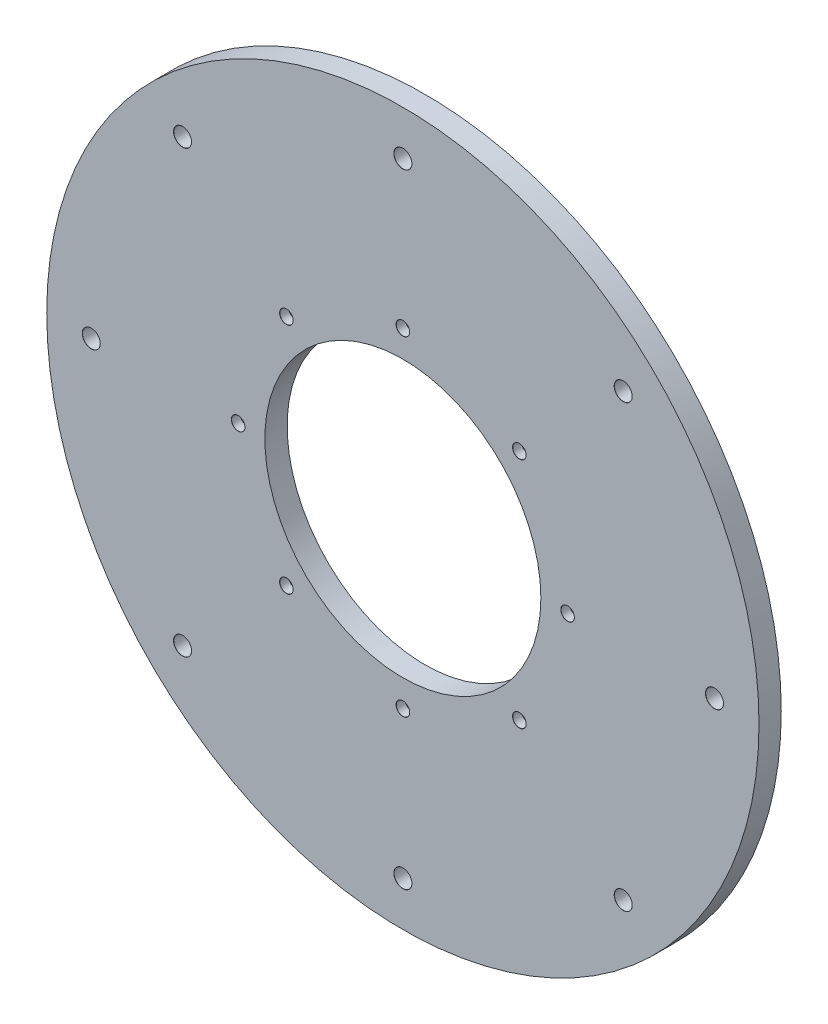
SolidWorks part; units mm, degrees
material "1.0503 (C45)"
ref_plane "Front Plane" through (0, 0, 0) normal (0, 0, 1) x (1, 0, 0)
ref_plane "Top Plane" through (0, 0, 0) normal (0, 1, 0) x (1, 0, 0)
ref_plane "Right Plane" through (0, 0, 0) normal (1, 0, 0) x (0, 0, -1)
sketch "Sketch2" plane through (0, 0, 0) normal (0, 0, 1) x (1, 0, 0)
  line L0 (0, 0) -> (0, 90.7247) construction
  circle A0 centre (0, 0) radius 80
  circle A1 centre (0, 0) radius 31
  point P0 (0, 0)
  point P4 (0, 70)
  point P5 (49.4975, 49.4975)
  point P8 (70, 0)
  point P9 (49.4975, -49.4975)
  point P10 (0, -70)
  point P11 (-49.4975, -49.4975)
  point P12 (-70, 0)
  point P13 (-49.4975, 49.4975)
  point P14 (0, 0)
  dimension "D3" = 160
  dimension "D4" = 62
  dimension "D1" = 70
  dimension "D2" = 8
extrude "Boss-Extrude1" add sketch "Sketch2" along normal blind 5
sketch "Sketch9" plane through (0, 0, 0) normal (0, 0, 1) x (1, 0, 0)
  line L0 (0, 0) -> (0, 90.7247) construction
  circle A0 centre (0, 0) radius 80
  circle A1 centre (0, 0) radius 31
  point P0 (0, 0)
  point P4 (0, 70)
  point P5 (49.4975, 49.4975)
  point P8 (70, 0)
  point P9 (49.4975, -49.4975)
  point P10 (0, -70)
  point P11 (-49.4975, -49.4975)
  point P12 (-70, 0)
  point P13 (-49.4975, 49.4975)
  point P14 (0, 0)
  dimension "D3" = 160
  dimension "D4" = 62
  dimension "D1" = 70
  dimension "D2" = 8
hole_wizard "Ø4.0mm Dowel Hole1" positions "Sketch10" profile "Sketch11" hole size "Ø4.0" standard "ISO"
sketch "Sketch10" plane through (0, 0, 5) normal (0, 0, 1) x (1, 0, 0)
  point P0 (0, 70)
  point P3 (-49.4975, 49.4975)
  point P6 (-70, 0)
  point P9 (-49.4975, -49.4975)
  point P12 (0, -70)
  point P15 (49.4975, -49.4975)
  point P18 (70, 0)
  point P21 (49.4975, 49.4975)
sketch "Sketch11" plane through (0, 70, 5) normal (1, 0, 0) x (0, -1, 0)
  line L0 (0, 0) -> (0, 6.2007)
  line L1 (0, 6.2007) -> (2, 4.999)
  line L2 (2, 4.999) -> (2, 0.025)
  line L3 (2, 0.025) -> (2.025, 0)
  line L5 (2.025, 0) -> (0, 0)
  line L6 (-2, 0.025) -> (-2.025, 0) construction
  line L10 (0, 6.2007) -> (-2, 4.999) construction
  line L11 (0, -6.35) -> (0, 107.95) construction
  dimension "Hole Dia." = 4
  dimension "Hole Depth" = 4.999
  dimension "Near C'Sink Dia." = 4.05
  dimension "Near C'Sink Angle" = 90
  dimension "Drill Angle" = 118
sketch "Sketch13" plane through (0, 0, 0) normal (0, 0, 1) x (1, 0, 0)
  line L0 (0, 0) -> (0, 102.9505) construction
  circle A0 centre (0, 37) radius 5
  circle A1 centre (26.163, 26.163) radius 5
  circle A2 centre (37, 0) radius 5
  circle A3 centre (26.163, -26.163) radius 5
  circle A4 centre (0, -37) radius 5
  circle A5 centre (-26.163, -26.163) radius 5
  circle A6 centre (-37, 0) radius 5
  circle A7 centre (-26.163, 26.163) radius 5
  point P3 (0, 37)
  point P4 (26.163, 26.163)
  point P7 (37, 0)
  point P8 (26.163, -26.163)
  point P9 (0, -37)
  point P10 (-26.163, -26.163)
  point P11 (-37, 0)
  point P12 (-26.163, 26.163)
  point P13 (0, 0)
  point P30 (0, 0)
  dimension "D3" = 8
  dimension "D1" = 37
  dimension "D2" = 8
hole_wizard "Ø3.0mm Dowel Hole1" positions "Sketch14" profile "Sketch15" hole size "Ø3.0" standard "ISO"
sketch "Sketch14" plane through (0, 0, 5) normal (0, 0, 1) x (1, 0, 0)
  point P0 (0, 37)
  point P3 (-26.163, 26.163)
  point P6 (-37, 0)
  point P9 (-26.163, -26.163)
  point P12 (0, -37)
  point P15 (26.163, -26.163)
  point P18 (37, 0)
  point P21 (26.163, 26.163)
sketch "Sketch15" plane through (0, 37, 5) normal (1, 0, 0) x (0, -1, 0)
  line L0 (0, 0) -> (0, 5.9003)
  line L1 (0, 5.9003) -> (1.5, 4.999)
  line L2 (1.5, 4.999) -> (1.5, 0.025)
  line L3 (1.5, 0.025) -> (1.525, 0)
  line L5 (1.525, 0) -> (0, 0)
  line L6 (-1.5, 0.025) -> (-1.525, 0) construction
  line L10 (0, 5.9003) -> (-1.5, 4.999) construction
  line L11 (0, -6.35) -> (0, 107.95) construction
  dimension "Hole Dia." = 3
  dimension "Hole Depth" = 4.999
  dimension "Near C'Sink Dia." = 3.05
  dimension "Near C'Sink Angle" = 90
  dimension "Drill Angle" = 118
extrude "Cut-Extrude1" cut sketch "Sketch13" along normal blind 3
